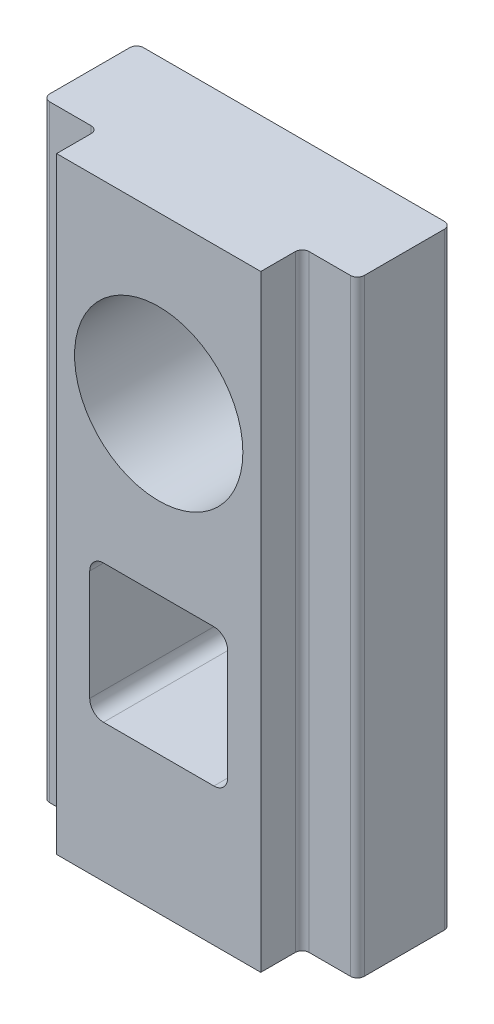
SolidWorks part; units mm, degrees
material "ABS"
ref_plane "Front Plane" through (0, 0, 0) normal (0, 0, 1) x (1, 0, 0)
ref_plane "Top Plane" through (0, 0, 0) normal (0, 1, 0) x (1, 0, 0)
ref_plane "Right Plane" through (0, 0, 0) normal (1, 0, 0) x (0, 0, -1)
sketch "Sketch1" plane through (0, 0, 0) normal (0, 1, 0) x (1, 0, 0)
  line L0 (0, 4) -> (0, -3.5298) construction
  line L1 (6, 4) -> (-6, 4) construction
  line L2 (-6, 4) -> (-6, 0) construction
  line L3 (-6, 0) -> (-4, 0) construction
  line L4 (-4, 0) -> (-4, -1.5) construction
  line L5 (-4, -1.5) -> (4, -1.5) construction
  line L6 (4, 0) -> (4, -1.5) construction
  line L7 (6, 0) -> (4, 0) construction
  line L8 (6, 4) -> (6, 0) construction
  line L9 (3.7, 0.3) -> (3.7, -1.2)
  line L10 (-3.7, -1.2) -> (3.7, -1.2)
  line L11 (-3.7, 0.3) -> (-3.7, -1.2)
  line L12 (-5.7, 0.3) -> (-3.7, 0.3)
  line L13 (-5.7, 3.7) -> (-5.7, 0.3)
  line L14 (5.7, 3.7) -> (-5.7, 3.7)
  line L15 (5.7, 3.7) -> (5.7, 0.3)
  line L16 (5.7, 0.3) -> (3.7, 0.3)
  point P10 (0, -1.5)
  dimension "D1" = 6
  dimension "D2" = 4
  dimension "D3" = 1.5
  dimension "D4" = 4
  dimension "D5" = 0.3
extrude "Boss-Extrude1" add sketch "Sketch1" against normal blind 22
sketch "Sketch2" plane through (0, 0, 1.2) normal (0, 0, 1) x (1, 0, 0)
  line L0 (0, 0) -> (0, -22) construction
  line L1 (-3.7, 0) -> (3.7, 0) construction
  line L2 (-3.7, -22) -> (3.7, -22) construction
  line L4 (-2.5, -12) -> (2.5, -12)
  line L5 (-2.5, -12) -> (-2.5, -17)
  line L6 (-2.5, -17) -> (2.5, -17)
  line L7 (2.5, -12) -> (2.5, -17)
  line L8 (-2.5, -12) -> (2.5, -17) construction
  line L9 (-2.5, -17) -> (2.5, -12) construction
  circle A0 centre (0, -6) radius 3.05
  circle A1 centre (0, -6) radius 4 construction
  point P9 (0, -14.5)
  point P13 (0, -10)
  dimension "D1" = 6.1
  dimension "D2" = 8
  dimension "D4" = 5
  dimension "D5" = 2
  dimension "D3" = 6
extrude "Cut-Extrude1" cut sketch "Sketch2" against normal through all
fillet "Fillet1" radius 0.25 6 edges at (5.7, -11, -3.7) (5.7, -11, -0.3) (3.7, -11, -0.3) (-3.7, -11, -0.3) (-5.7, -11, -0.3) (-5.7, -11, -3.7)
fillet "Fillet2" radius 0.5 4 edges at (2.5, -17, -1.25) (-2.5, -17, -1.25) (-2.5, -12, -1.25) (2.5, -12, -1.25)
